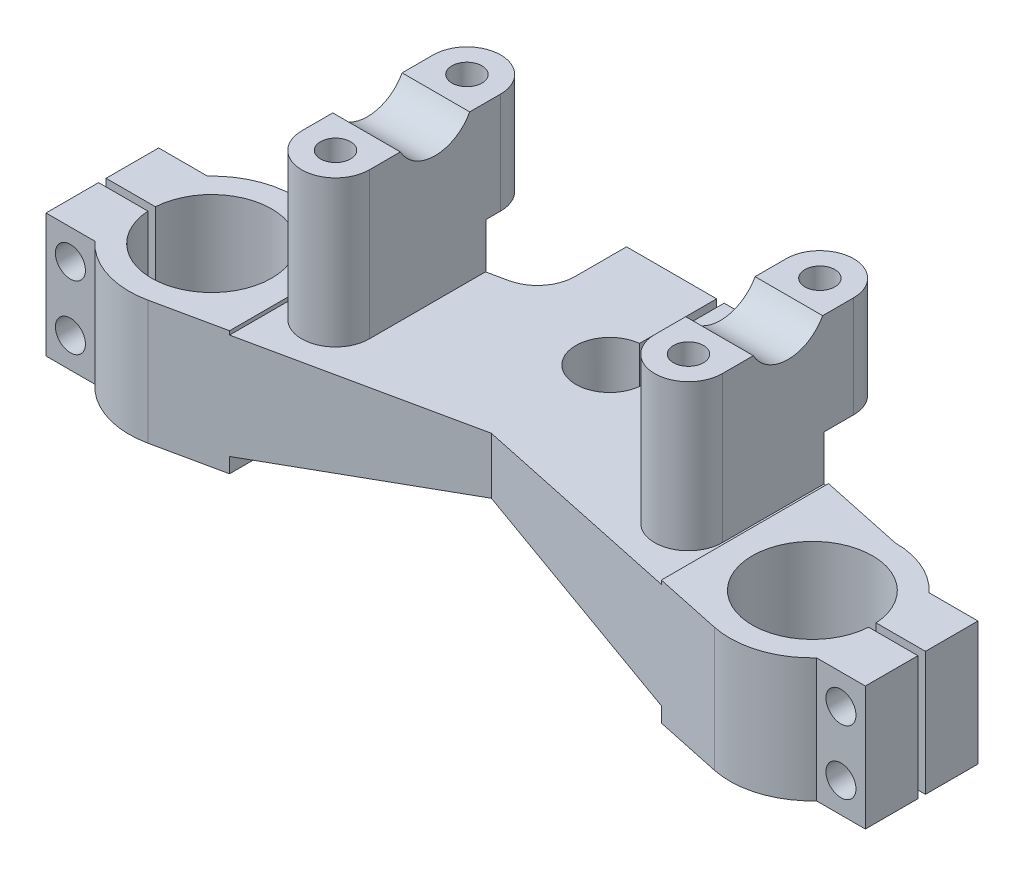
SolidWorks part; units mm, degrees
ref_plane "Front Plane" through (0, 0, 0) normal (0, 0, 1) x (1, 0, 0)
ref_plane "Top Plane" through (0, 0, 0) normal (0, 1, 0) x (1, 0, 0)
ref_plane "Right Plane" through (0, 0, 0) normal (1, 0, 0) x (0, 0, -1)
sketch "Sketch1" plane through (0, 0, 0) normal (0, 1, 0) x (1, 0, 0)
  line L0 (-25, 55.5) -> (-25, 33.6961)
  line L1 (-109.1052, 1) -> (-109.1052, 15)
  line L2 (-80, 22.0086) -> (-25, 33.6961)
  line L3 (-75.4253, -21.5279) -> (0, -5.5)
  line L4 (25, 55.5) -> (1, 55.5)
  line L5 (-109.1052, -1) -> (-109.1052, -15)
  line L6 (-109.1052, -15) -> (-96.1052, -15)
  line L7 (-109.1052, 15) -> (-96.1052, 15)
  line L8 (-1, 55.5) -> (-25, 55.5)
  line L9 (75.4253, -21.5279) -> (0, -5.5)
  line L10 (109.1052, 15) -> (96.1052, 15)
  line L11 (109.1052, -15) -> (96.1052, -15)
  line L12 (109.1052, -1) -> (109.1052, -15)
  line L13 (80, 22.0086) -> (25, 33.6961)
  line L14 (109.1052, 1) -> (109.1052, 15)
  line L15 (25, 55.5) -> (25, 33.6961)
  line L16 (-109.1052, 1) -> (-95.9687, 1)
  line L17 (-109.1052, -1) -> (-95.9687, -1)
  line L18 (109.1052, 1) -> (95.9687, 1)
  line L19 (109.1052, -1) -> (95.9687, -1)
  line L20 (-1, 55.5) -> (-1, 34.9443)
  line L21 (1, 55.5) -> (1, 34.9443)
  arc A0 (-95.9687, -1) -> (-95.9687, 1) centre (-80, 0) ccw
  arc A1 (-96.1052, -15) -> (-75.4253, -21.5279) centre (-80, 0) ccw
  arc A2 (80, 22.0086) -> (96.1052, 15) centre (80, 0) cw
  arc A3 (95.9687, -1) -> (95.9687, 1) centre (80, 0) cw
  arc A4 (-1, 34.9443) -> (1, 34.9443) centre (0, 26) ccw
  arc A5 (-80, 22.0086) -> (-96.1052, 15) centre (-80, 0) ccw
  arc A6 (96.1052, -15) -> (75.4253, -21.5279) centre (80, 0) cw
  dimension "D1" = 32
  dimension "D4" = 18
  dimension "D2" = 80
  dimension "D6" = 31.5
  dimension "D7" = 13
extrude "Boss-Extrude1" add sketch "Sketch1" along normal blind 33
fillet "Fillet2" radius 10 1 edges at (25, 16.5, -33.6961)
fillet "Fillet3" radius 10 1 edges at (-25, 16.5, -33.6961)
sketch "Sketch2" plane through (0, 0, 0) normal (0, 0, 1) x (1, 0, 0)
sketch "Sketch3" plane through (0, 0, 0) normal (0, 0, 1) x (1, 0, 0)
  line L0 (-75.4253, 33) -> (-75.4253, 0) construction
  line L1 (0, 38.6509) -> (0, -6.0963) construction
  line L2 (57.5, 32) -> (-57.5, 32)
  line L4 (-57.5, 32) -> (-57.5, 36.9107)
  line L5 (-57.5, 36.9107) -> (57.5, 36.9107)
  line L6 (57.5, 32) -> (57.5, 36.9107)
  line L7 (-57.5, 4) -> (-57.5, -3.2983)
  line L8 (-57.5, -3.2983) -> (57.5, -3.2983)
  line L9 (-57.5, 4) -> (0, 17)
  line L10 (57.5, 4) -> (57.5, -3.2983)
  line L11 (57.5, 4) -> (0, 17)
  point P14 (0, 32)
  point P15 (0, 36.9107)
  point P20 (0, -3.2983)
  dimension "D1" = 33
  dimension "D2" = 57.5
  dimension "D3" = 1
extrude "Cut-Extrude1" cut sketch "Sketch3" against normal through all both and the other way through all
ref_plane "Plane1" through (0, 71, 0) normal (0, 1, 0) x (1, 0, 0)
sketch "Sketch5" plane through (0, 71, 0) normal (0, 1, 0) x (1, 0, 0)
  line L0 (-38, 0) -> (-38, 35)
  line L1 (-56, 0) -> (-56, 35)
  line L3 (56, 0) -> (56, 35)
  line L4 (38, 0) -> (38, 35)
  arc A0 (-56, 0) -> (-38, 0) centre (-47, 0) ccw
  arc A1 (-38, 35) -> (-56, 35) centre (-47, 35) ccw
  arc A2 (38, 35) -> (56, 35) centre (47, 35) cw
  arc A3 (56, 0) -> (38, 0) centre (47, 0) cw
  dimension "D2" = 18
  dimension "D1" = 47
  dimension "D3" = 2
extrude "Boss-Extrude3" add sketch "Sketch5" against normal blind 39
sketch "Sketch6" plane through (0, 0, 0) normal (1, 0, 0) x (0, 0, -1)
  line L0 (44, 71) -> (44, 44)
  line L1 (44, 32) -> (44, 71) construction
  line L2 (44, 32) -> (31.0543, 32)
  line L3 (27.1086, 32) -> (35, 32) construction
  line L4 (31.0543, 32) -> (31.0543, 44)
  line L5 (35, 32) -> (44, 32) construction
  line L6 (55.5, 32) -> (41.7944, 32) construction
  line L7 (44, 32) -> (62.9181, 32)
  line L8 (62.9181, 32) -> (62.9181, 71)
  line L9 (62.9181, 71) -> (44, 71)
  line L10 (31.0543, 44) -> (44, 44)
  dimension "D1" = 27
extrude "Cut-Extrude5" cut sketch "Sketch6" against normal mid plane 131
sketch "Sketch7" plane through (0, 0, 0) normal (0, 1, 0) x (1, 0, 0)
  line L0 (-56, 31.0543) -> (-38, 31.0543)
  line L1 (-56, 31.0543) -> (-38, 31.0543) construction
  line L2 (-56, 31.0543) -> (-38, 31.0543) construction
  line L3 (-38, 31.0543) -> (-56, 27.1086)
  line L4 (-56, 27.1086) -> (-56, 31.0543)
  line L6 (56, 27.1086) -> (56, 31.0543)
  line L7 (38, 31.0543) -> (56, 27.1086)
  line L8 (56, 31.0543) -> (38, 31.0543)
extrude "Cut-Extrude6" cut sketch "Sketch7" along normal blind 44
sketch "Sketch9" plane through (0, 71, 0) normal (0, 1, 0) x (1, 0, 0)
  circle A0 centre (-47, 0) radius 4
  circle A1 centre (-47, 35) radius 4
  circle A2 centre (47, 0) radius 4
  circle A3 centre (47, 35) radius 4
  dimension "D1" = 8
  dimension "D2" = 8
  dimension "D3" = 8
  dimension "D4" = 8
extrude "Cut-Extrude7" cut sketch "Sketch9" against normal blind 44
sketch "Sketch10" plane through (0, 0, 0) normal (0, 0, 1) x (1, 0, 0)
  circle A0 centre (-102.6052, 8) radius 4
  circle A1 centre (-102.6052, 25) radius 4
  circle A2 centre (102.6052, 8) radius 4
  circle A3 centre (102.6052, 25) radius 4
  dimension "D1" = 8
  dimension "D2" = 8
extrude "Cut-Extrude8" cut sketch "Sketch10" against normal mid plane 44
sketch "Sketch11" plane through (0, 0, 0) normal (1, 0, 0) x (0, 0, -1)
  circle A0 centre (48.6472, 21.6739) radius 4
  dimension "D1" = 8
extrude "Cut-Extrude9" cut sketch "Sketch11" against normal mid plane 62
sketch "Sketch12" plane through (0, 0, 0) normal (1, 0, 0) x (0, 0, -1)
  line L0 (35, 71) -> (0, 71) construction
  circle A0 centre (17.5, 76) radius 10.5
  point P4 (17.5, 71)
  dimension "D1" = 21
  dimension "D2" = 5
extrude "Cut-Extrude10" cut sketch "Sketch12" against normal mid plane 213 contours A0
